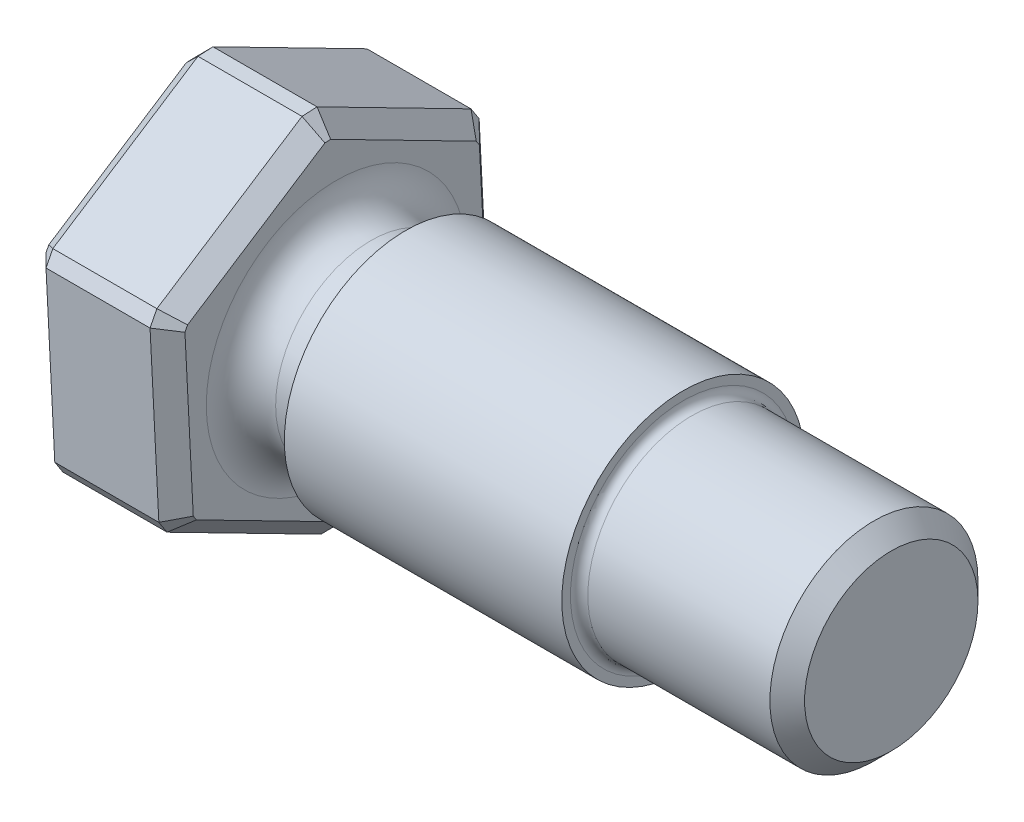
SolidWorks part; units mm, degrees
material "C40 or 38NiCrMo4"
ref_plane "Piano frontale" through (0, 0, 0) normal (0, 0, 1) x (1, 0, 0)
ref_plane "Piano superiore" through (0, 0, 0) normal (0, 1, 0) x (1, 0, 0)
ref_plane "Piano destro" through (0, 0, 0) normal (1, 0, 0) x (0, 0, -1)
sketch "Schizzo1" plane through (0, 0, 0) normal (1, 0, 0) x (0, 0, -1)
  circle A0 centre (0, 0) radius 7
extrude "Estrusione1" add sketch "Schizzo1" along normal blind 20
cosmetic thread "Filettatura cosmetica2"
sketch "Schizzo2" plane through (20, 0, 0) normal (1, 0, 0) x (0, 0, -1)
  circle A0 centre (0, 0) radius 6
extrude "Estrusione2" add sketch "Schizzo2" along normal blind 12
sketch "Schizzo3" plane through (0, 0, 0) normal (-1, 0, 0) x (0, 0, 1)
  line L1 (9.2087, -5.9609) -> (9.7667, 4.9945)
  line L2 (9.7667, 4.9945) -> (0.5579, 10.9555)
  line L3 (0.5579, 10.9555) -> (-9.2087, 5.9609)
  line L4 (-9.2087, 5.9609) -> (-9.7667, -4.9945)
  line L5 (-9.7667, -4.9945) -> (-0.5579, -10.9555)
  line L6 (-0.5579, -10.9555) -> (9.2087, -5.9609)
  circle A0 centre (0, 0) radius 9.5 construction
extrude "Estrusione3" add sketch "Schizzo3" along normal blind 8
sketch "Schizzo4" plane through (0, 0, 0) normal (1, 0, 0) x (0, 0, -1)
  circle A0 centre (0, 0) radius 5.5
extrude "Estrusione4" cut sketch "Schizzo4" along normal blind 4 flip side to cut
chamfer "Smusso1" distance 0.5 angle 30 6 edges at (-4, -10.9555, -0.5579) (-4, -4.9945, -9.7667) (-4, 5.9609, -9.2087) (-4, 10.9555, 0.5579) (-4, -5.9609, 9.2087) (-4, 4.9945, 9.7667)
chamfer "Smusso2" distance 1 angle 45 24 edges at (-8, -4.8807, -9.5441) (-8, 0.4832, -9.4877) (-8, 5.8251, -8.9989) (-8, 8.4582, -4.3254) (-8, 10.7058, 0.5452) (-8, 7.975, 5.1623) (-8, 4.8807, 9.5441) (-8, -0.4832, 9.4877) (-8, -5.8251, 8.9989) (-8, -8.4582, 4.3254) (-8, -10.7058, -0.5452) (-8, -7.975, -5.1623) (0, -5.8251, 8.9989) (0, -0.4832, 9.4877) (0, 4.8807, 9.5441) (0, 7.975, 5.1623) (0, 10.7058, 0.5452) (0, 8.4582, -4.3254) (0, 5.8251, -8.9989) (0, 0.4832, -9.4877) (0, -4.8807, -9.5441) (0, -7.975, -5.1623) (0, -10.7058, -0.5452) (0, -8.4582, 4.3254)
fillet "Raccordo1" radius 2 1 edges at (0, 0, -5.5)
fillet "Raccordo2" radius 0.5 2 edges at (20, 0, -6) (4, 0, -5.5)
chamfer "Smusso3" distance 1 angle 45 1 edges at (32, 0, -6)
